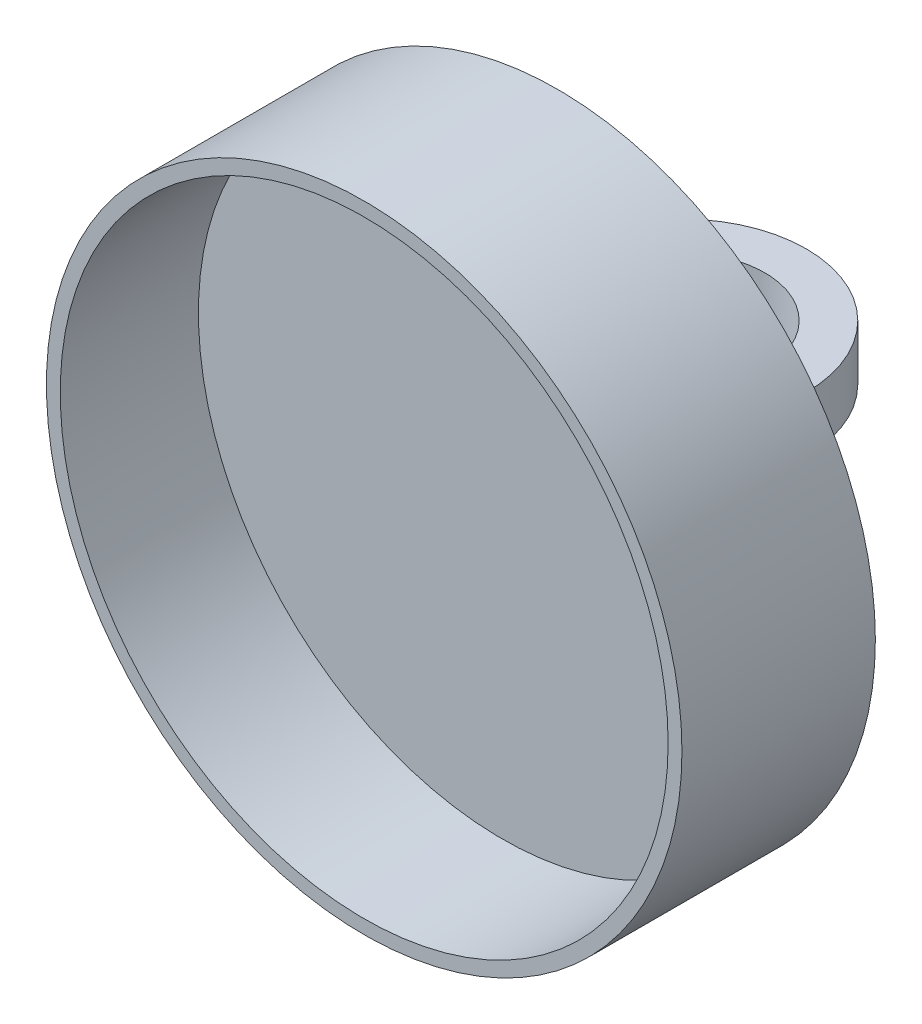
SolidWorks part; units mm, degrees
ref_plane "Front Plane" through (0, 0, 0) normal (0, 0, 1) x (1, 0, 0)
ref_plane "Top Plane" through (0, 0, 0) normal (0, 1, 0) x (1, 0, 0)
ref_plane "Right Plane" through (0, 0, 0) normal (1, 0, 0) x (0, 0, -1)
sketch "Sketch1" plane through (0, 0, 0) normal (0, 0, 1) x (1, 0, 0)
  circle A0 centre (0, 0) radius 11.5
  dimension "D1" = 23
extrude "Boss-Extrude1" add sketch "Sketch1" along normal blind 2
sketch "Sketch2" plane through (0, 0, 2) normal (0, 0, 1) x (1, 0, 0)
  circle A0 centre (0, 0) radius 11
  circle A1 centre (0, 0) radius 11.5
  dimension "D1" = 23
  dimension "D2" = 22
extrude "Boss-Extrude2" add sketch "Sketch2" along normal blind 5
sketch "Sketch3" plane through (0, 0, 0) normal (0, 1, 0) x (1, 0, 0)
  line L0 (0, 0) -> (0, 4.5) construction
  circle A0 centre (0, 4.5) radius 4.5
  circle A1 centre (0, 4.5) radius 3
  dimension "D2" = 9
  dimension "D3" = 6
  dimension "D1" = 4.5
extrude "Boss-Extrude3" add sketch "Sketch3" along normal blind 2
